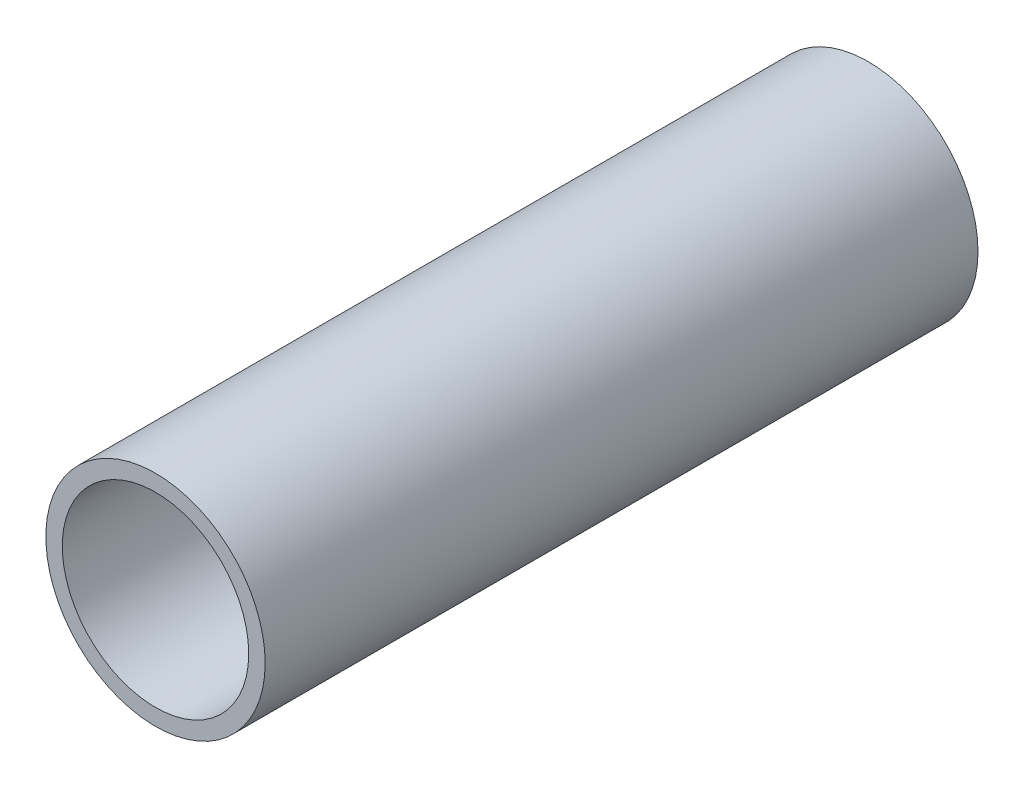
SolidWorks part; units mm, degrees
ref_plane "Front Plane" through (0, 0, 0) normal (0, 0, 1) x (1, 0, 0)
ref_plane "Top Plane" through (0, 0, 0) normal (0, 1, 0) x (1, 0, 0)
ref_plane "Right Plane" through (0, 0, 0) normal (1, 0, 0) x (0, 0, -1)
sketch "Sketch1" plane through (0, 0, 0) normal (0, 0, 1) x (1, 0, 0)
  circle A0 centre (0, 0) radius 8.5
  circle A1 centre (0, 0) radius 10
  dimension "D1" = 17
  dimension "D2" = 20
extrude "Boss-Extrude1" add sketch "Sketch1" along normal blind 65
